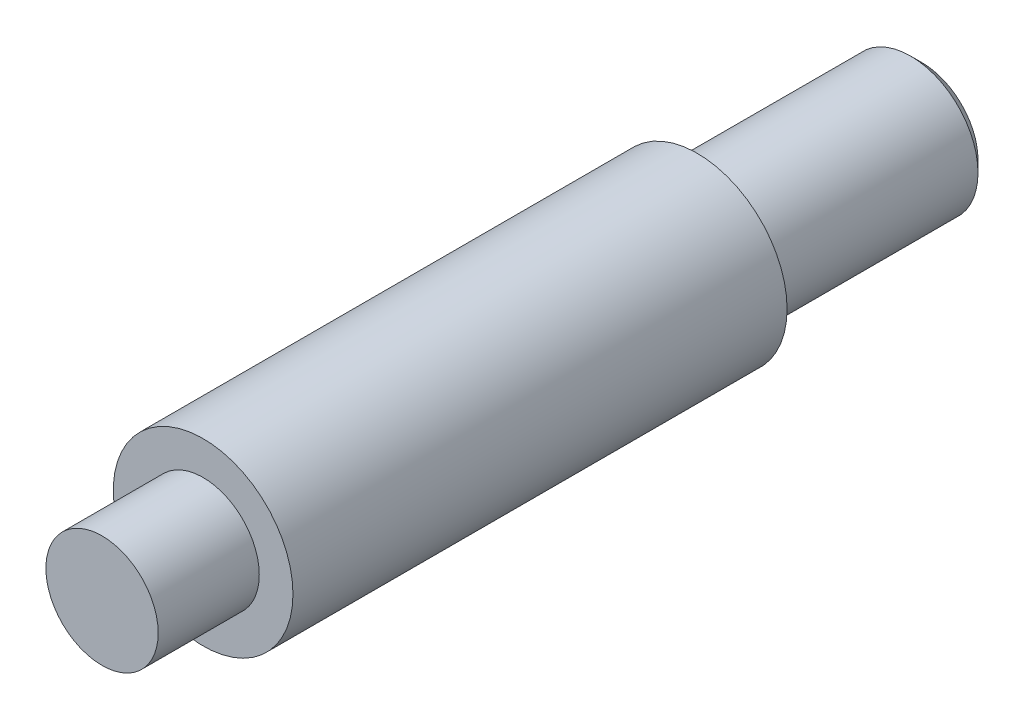
SolidWorks part; units mm, degrees
ref_plane "GAUCHE" through (0, 0, 0) normal (0, 0, 1) x (1, 0, 0)
ref_plane "Plan2" through (0, 0, 0) normal (0, 1, 0) x (1, 0, 0)
ref_plane "Plan3" through (0, 0, 0) normal (1, 0, 0) x (0, 0, -1)
sketch "Esquisse1" plane through (0, 0, 0) normal (0, 0, 1) x (1, 0, 0)
  circle A0 centre (0, 0) radius 8
  dimension "D1" = 16
extrude "Base-Extrusion" add sketch "Esquisse1" along normal blind 44
sketch "Esquisse2" plane through (0, 0, 44) normal (0, 0, 1) x (1, 0, 0)
  circle A0 centre (0, 0) radius 5
  circle A1 centre (0, 0) radius 8 construction
  dimension "D1" = 10
extrude "Boss.-Extru.1" add sketch "Esquisse2" along normal blind 9
sketch "Esquisse3" plane through (0, 0, 0) normal (0, 0, -1) x (-1, 0, 0)
  circle A0 centre (0, 0) radius 6
  dimension "D1" = 12
extrude "Boss.-Extru.2" add sketch "Esquisse3" along normal blind 20
chamfer "Chanfrein1" distance 1 angle 45
